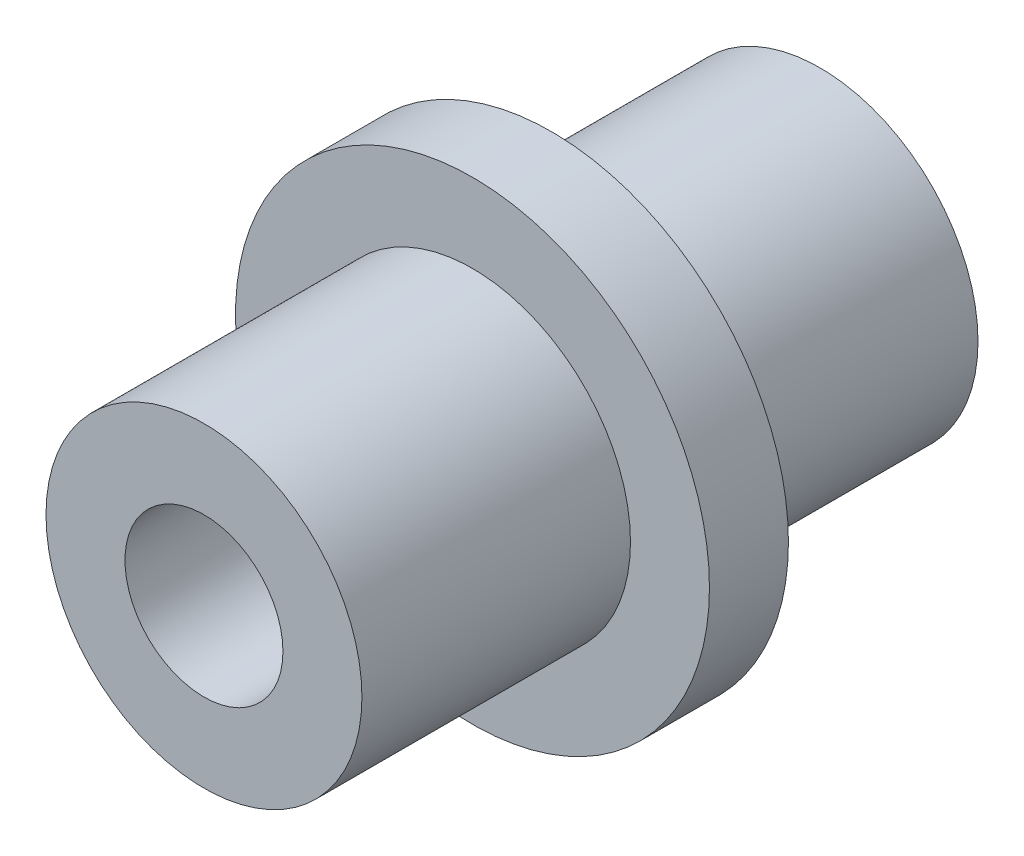
SolidWorks part; units mm, degrees
ref_plane "Front Plane" through (0, 0, 0) normal (0, 0, 1) x (1, 0, 0)
ref_plane "Top Plane" through (0, 0, 0) normal (0, 1, 0) x (1, 0, 0)
ref_plane "Right Plane" through (0, 0, 0) normal (1, 0, 0) x (0, 0, -1)
sketch "Flange Sketch" plane through (0, 0, 0) normal (0, 0, 1) x (1, 0, 0)
  circle A0 centre (0, 0) radius 3
  dimension "D1" = 6
extrude "Flange Extrude" add sketch "Flange Sketch" along normal mid plane 1
sketch "Joint Sketch" plane through (0, 0, 0.5) normal (0, 0, 1) x (1, 0, 0)
  circle A0 centre (0, 0) radius 2
  dimension "D1" = 4
extrude "Joint Extrude" add sketch "Joint Sketch" along normal blind 3.4
mirror "Joint Mirror" about plane through (0, 0, 0) normal (0, 0, 1) of "Joint Extrude"
sketch "Hole Sketch" plane through (0, 0, 3.9) normal (0, 0, 1) x (1, 0, 0)
  circle A0 centre (0, 0) radius 1
  dimension "D1" = 2
extrude "Hole Extrude" cut sketch "Hole Sketch" against normal through all
equation "\"Joint Diameter\"= 4"
equation "\"Flange Diameter\"= 6"
equation "\"Bolt Diameter\"= 2"
equation "\"Joint Length\"= 3.4"
equation "\"Flange Length\"= 1"
equation "\"D1@Flange Sketch\" = \"Flange Diameter\""
equation "\"D1@Flange Extrude\" = \"Flange Length\""
equation "\"D1@Joint Sketch\" = \"Joint Diameter\""
equation "\"D1@Joint Extrude\" = \"Joint Length\""
equation "\"D1@Hole Sketch\" = \"Bolt Diameter\""
